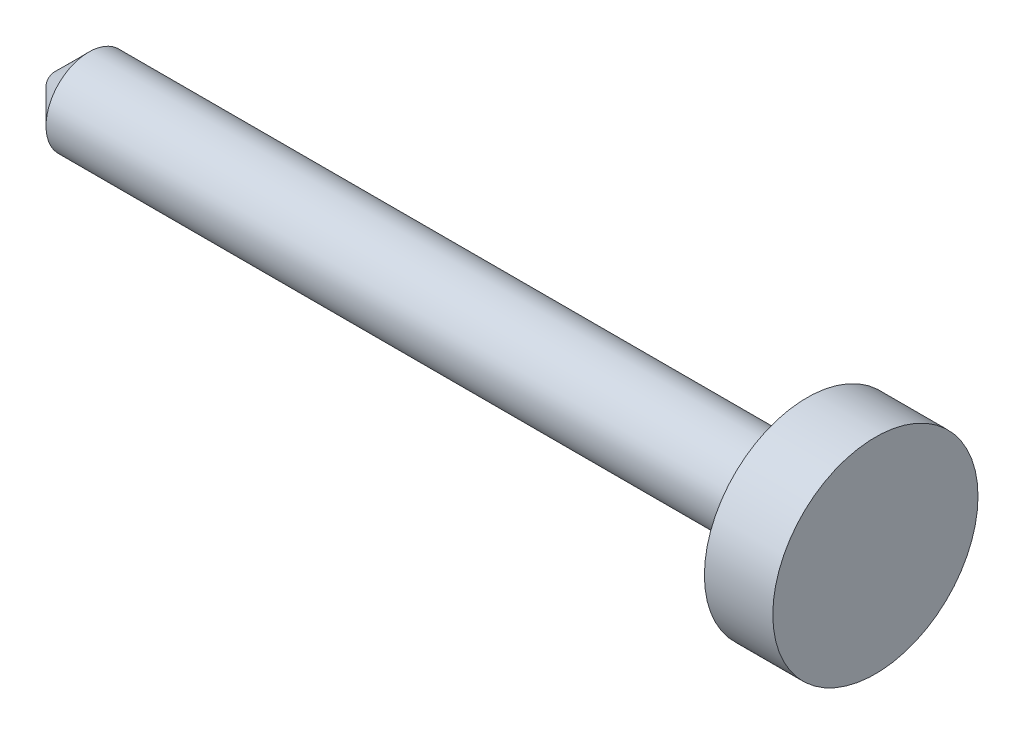
SolidWorks part; units mm, degrees
ref_plane "Front Plane" through (0, 0, 0) normal (0, 0, 1) x (1, 0, 0)
ref_plane "Top Plane" through (0, 0, 0) normal (0, 1, 0) x (1, 0, 0)
ref_plane "Right Plane" through (0, 0, 0) normal (1, 0, 0) x (0, 0, -1)
sketch "Sketch1" plane through (0, 0, 0) normal (0, 0, 1) x (1, 0, 0)
  line L0 (-16.463, 0) -> (7.537, 0) construction
  line L1 (-16.463, 0) -> (-16.463, 1.25)
  line L2 (-16.463, 1.25) -> (5.537, 1.25)
  line L3 (5.537, 1.25) -> (5.537, 3)
  line L4 (5.537, 3) -> (7.537, 3)
  line L5 (7.537, 3) -> (7.537, 0)
  line L6 (7.537, 0) -> (-16.463, 0)
  dimension "D1" = 3
  dimension "D2" = 1.25
  dimension "D3" = 24
  dimension "D4" = 2
revolve "Revolve1" add sketch "Sketch1" angle 360 about L0
chamfer "Chamfer2" distance 1 angle 45 1 edges at (-16.463, 0, 1.25)
